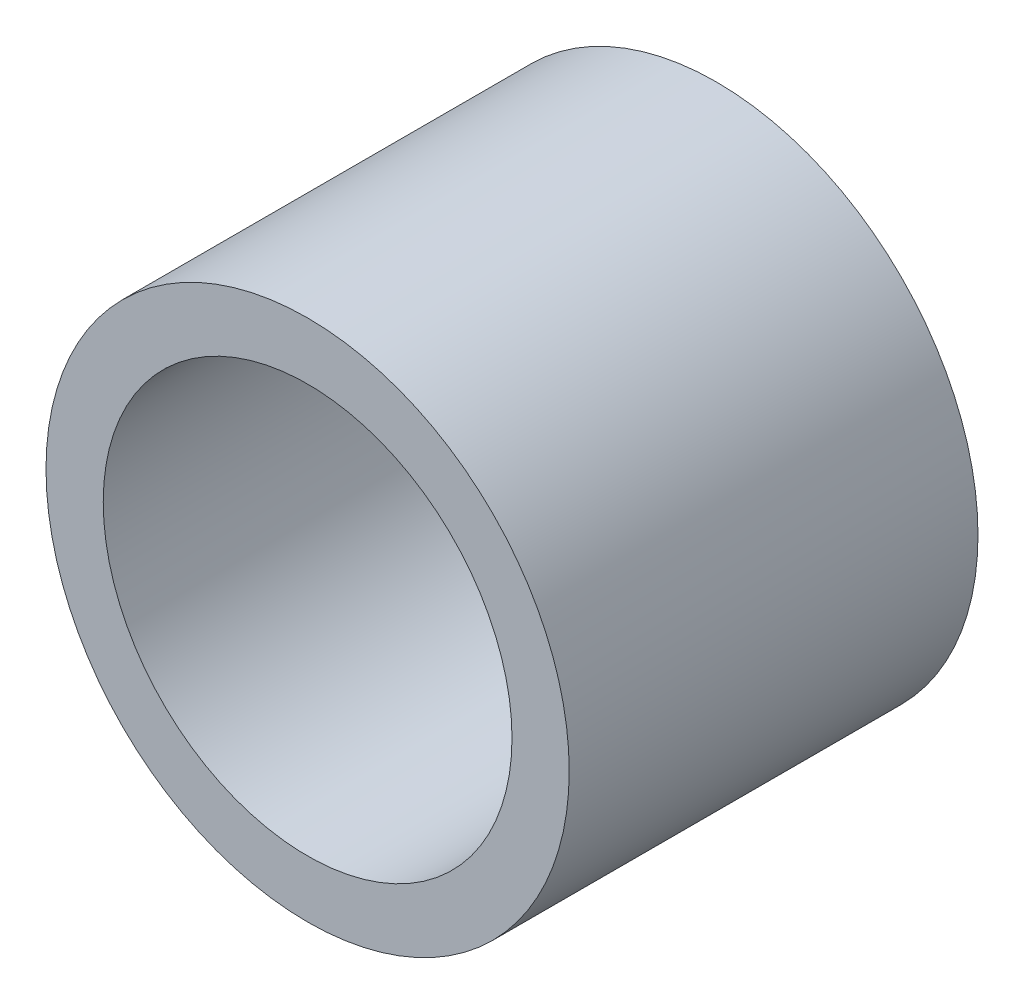
SolidWorks part; units mm, degrees
ref_plane "Front Plane" through (0, 0, 0) normal (0, 0, 1) x (1, 0, 0)
ref_plane "Top Plane" through (0, 0, 0) normal (0, 1, 0) x (1, 0, 0)
ref_plane "Right Plane" through (0, 0, 0) normal (1, 0, 0) x (0, 0, -1)
sketch "Sketch1" plane through (0, 0, 0) normal (0, 0, 1) x (1, 0, 0)
  circle A0 centre (0, 0) radius 3.175
  circle A1 centre (0, 0) radius 4.064
  dimension "D1" = 8.128
  dimension "D2" = 6.35
extrude "Extrude1" add sketch "Sketch1" along normal blind 6.35
